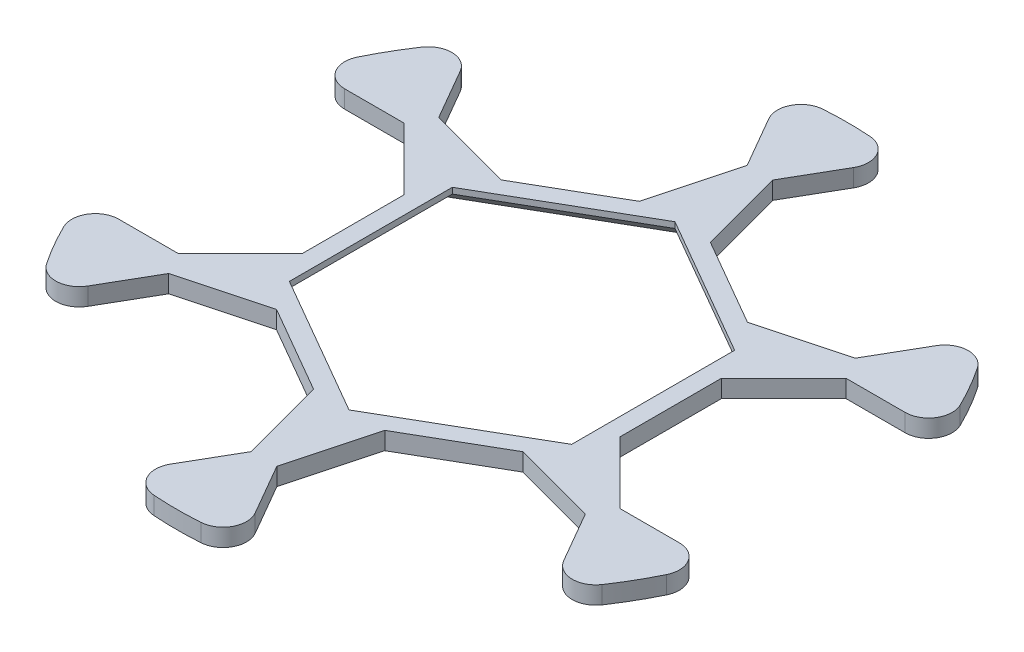
SolidWorks part; units mm, degrees
ref_plane "Front Plane" through (0, 0, 0) normal (0, 0, 1) x (1, 0, 0)
ref_plane "Top Plane" through (0, 0, 0) normal (0, 1, 0) x (1, 0, 0)
ref_plane "Right Plane" through (0, 0, 0) normal (1, 0, 0) x (0, 0, -1)
sketch "Sketch1" plane through (0, 0, 0) normal (0, 1, 0) x (1, 0, 0)
  circle A0 centre (0, 0) radius 28.5
  circle A1 centre (0, 0) radius 12.7
  dimension "D1" = 57
  dimension "D2" = 25.4
extrude "Boss-Extrude1" add sketch "Sketch1" along normal blind 2
sketch "Sketch2" plane through (0, 2, 0) normal (0, 1, 0) x (1, 0, 0)
  circle A1 centre (0, 0) radius 28.5 construction
  circle A2 centre (0, 0) radius 28.5
extrude "Boss-Extrude2" add sketch "Sketch2" along normal blind 1
sketch "Sketch3" plane through (0, 3, 0) normal (0, 1, 0) x (1, 0, 0)
  circle A0 centre (0, 0) radius 11
  dimension "D1" = 22
extrude "Boss-Extrude3" add sketch "Sketch3" along normal blind 7
sketch "Sketch4" plane through (0, 10, 0) normal (0, 1, 0) x (1, 0, 0)
  circle A0 centre (0, 0) radius 9.65
  dimension "D1" = 19.3
extrude "Cut-Extrude1" cut sketch "Sketch4" against normal through all both and the other way through all
sketch "Sketch5" plane through (0, 10, 0) normal (0, 1, 0) x (1, 0, 0)
  circle A0 centre (0, 0) radius 11
  circle A1 centre (0, 0) radius 8
  dimension "D1" = 16
extrude "Boss-Extrude4" add sketch "Sketch5" along normal blind 5
sketch "Sketch6" plane through (0, 2, 0) normal (0, -1, 0) x (1, 0, 0)
  circle A0 centre (0, 0) radius 9.65 construction
  circle A1 centre (0, 0) radius 12.7
  circle A2 centre (0, 0) radius 12.7
  circle A3 centre (0, 0) radius 9.65
  dimension "D1" = 0
extrude "Boss-Extrude5" add sketch "Sketch6" along normal up to surface (2 mm away) up to face at (0, 0, 28.5)
sketch "Sketch11" plane through (0, 3, 0) normal (0, 1, 0) x (1, 0, 0)
  line L1 (-14.6647, 0) -> (-7.3323, -12.7)
  line L2 (-7.3323, -12.7) -> (7.3323, -12.7)
  line L3 (7.3323, -12.7) -> (14.6647, 0)
  line L4 (14.6647, 0) -> (7.3323, 12.7)
  line L5 (7.3323, 12.7) -> (-7.3323, 12.7)
  line L6 (-7.3323, 12.7) -> (-14.6647, 0)
  circle A0 centre (0, 0) radius 12.7 construction
  circle A1 centre (0, 0) radius 11 construction
  circle A2 centre (0, 0) radius 11
  dimension "D1" = 25.4
sketch "Sketch13" plane through (0, 0, 0) normal (0, -1, 0) x (1, 0, 0)
  circle A1 centre (0, 0) radius 28.5
  circle A2 centre (0, 0) radius 28.5
  dimension "D1" = 0
extrude "Cut-Extrude2" cut sketch "Sketch13" against normal blind 1
sketch "Sketch12" plane through (0, 1, 0) normal (0, -1, 0) x (1, 0, 0)
  line L0 (25.5, 0) -> (-25.5, 0) construction
  line L2 (26.5, -2) -> (24.5, -2)
  line L3 (26.5, -2) -> (26.5, 2)
  line L4 (26.5, 2) -> (24.5, 2)
  line L5 (24.5, -2) -> (24.5, 2)
  line L6 (26.5, -2) -> (24.5, 2) construction
  line L7 (26.5, 2) -> (24.5, -2) construction
  line L8 (-26.5, -2) -> (-24.5, -2)
  line L9 (-26.5, -2) -> (-26.5, 2)
  line L10 (-26.5, 2) -> (-24.5, 2)
  line L11 (-24.5, -2) -> (-24.5, 2)
  line L12 (-26.5, -2) -> (-24.5, 2) construction
  line L13 (-26.5, 2) -> (-24.5, -2) construction
  point P4 (0, 0)
  dimension "D1" = 51
  dimension "D2" = 2
  dimension "D3" = 4
  dimension "D4" = 2
  dimension "D5" = 4
extrude "Boss-Extrude7" add sketch "Sketch12" along normal blind 2
fillet "Fillet1" radius 0.5 8 edges at (-26.5, 0, 2) (-26.5, 0, -2) (-24.5, 0, -2) (-24.5, 0, 2) (26.5, 0, 2) (26.5, 0, -2) (24.5, 0, -2) (24.5, 0, 2)
sketch "Sketch14" plane through (0, 3, 0) normal (0, 1, 0) x (1, 0, 0)
  circle A0 centre (0, 0) radius 11 construction
  circle A1 centre (0, 0) radius 28.5
  circle A2 centre (0, 0) radius 28.5
  circle A3 centre (0, 0) radius 11
  dimension "D1" = 0
extrude "Boss-Extrude8" add sketch "Sketch14" along normal blind 0.35
sketch "Sketch15" plane through (0, 3.35, 0) normal (0, 1, 0) x (1, 0, 0)
  line L1 (0, -12.9904) -> (11.25, -6.4952)
  line L2 (11.25, -6.4952) -> (11.25, 6.4952)
  line L3 (11.25, 6.4952) -> (0, 12.9904)
  line L4 (0, 12.9904) -> (-11.25, 6.4952)
  line L5 (-11.25, 6.4952) -> (-11.25, -6.4952)
  line L6 (-11.25, -6.4952) -> (0, -12.9904)
  circle A0 centre (0, 0) radius 11.25 construction
  circle A2 centre (0, 0) radius 9.65 construction
  circle A3 centre (0, 0) radius 9.65
  dimension "D1" = 22.5
extrude "Boss-Extrude9" add sketch "Sketch15" along normal up to surface (11.65 mm away) up to face at (0, 15, 11)
sketch "Sketch16" plane through (0, 3.35, 0) normal (0, 1, 0) x (1, 0, 0)
  line L0 (0, 0) -> (0, -28.5) construction
  line L1 (0, 0) -> (-11.25, -6.4952) construction
  line L2 (-11.25, -6.4952) -> (-24.6817, -14.25) construction
  line L3 (0, -28.5) -> (-24.6817, -14.25) construction
  line L4 (-14.25, -24.6817) -> (-6.75, -11.6913) construction
  line L5 (-12.3409, -21.375) -> (-14.25, -24.6817) construction
  line L6 (-6.3692, -29.2317) -> (-22.1308, -20.1317) construction
  line L8 (-6.3692, -29.2317) -> (-2.3692, -22.3035) construction
  line L10 (-2.3692, -22.3035) -> (-4.1993, -15.4734) construction
  line L11 (-11.3007, -11.3734) -> (-18.1308, -13.2035) construction
  line L12 (-6.1862, -29.9147) -> (-22.8138, -20.3147)
  line L13 (-4.1993, -15.4734) -> (-11.3007, -11.3734) construction
  line L14 (-18.1308, -13.2035) -> (-22.1308, -20.1317) construction
  line L17 (-3.7699, -15.1439) -> (-11.2301, -10.8368) construction
  line L50 (-3.7699, -15.1439) -> (-11.2301, -10.8368) construction
  line L51 (-11.2301, -10.8368) -> (-18.4603, -12.7742) construction
  line L52 (-1.8326, -22.3742) -> (-3.7699, -15.1439) construction
  line L53 (-3.0261, -13.8413) -> (-10.4739, -9.5413)
  line L54 (-10.4739, -9.5413) -> (-17.7138, -11.4813)
  line L55 (-3.0261, -13.8413) -> (-1.0862, -21.0813)
  line L56 (-22.8138, -20.3147) -> (-17.7138, -11.4813)
  line L57 (-6.1862, -29.9147) -> (-1.8326, -22.3742) construction
  line L58 (-18.4603, -12.7742) -> (-22.8138, -20.3147) construction
  line L59 (-6.1862, -29.9147) -> (-1.0862, -21.0813)
  line L60 (-13.5, -4.3) -> (-18.8, -9.6)
  line L61 (-29, -9.6) -> (-18.8, -9.6)
  line L62 (-29, -9.6) -> (-29, 9.6)
  line L63 (-29, 9.6) -> (-18.8, 9.6)
  line L64 (-13.5, 4.3) -> (-18.8, 9.6)
  line L65 (-13.5, -4.3) -> (-13.5, 4.3)
  line L66 (-10.4739, 9.5413) -> (-17.7138, 11.4813)
  line L67 (-22.8138, 20.3147) -> (-17.7138, 11.4813)
  line L68 (-22.8138, 20.3147) -> (-6.1862, 29.9147)
  line L69 (-6.1862, 29.9147) -> (-1.0862, 21.0813)
  line L70 (-3.0261, 13.8413) -> (-1.0862, 21.0813)
  line L71 (-10.4739, 9.5413) -> (-3.0261, 13.8413)
  line L72 (3.0261, 13.8413) -> (1.0862, 21.0813)
  line L73 (6.1862, 29.9147) -> (1.0862, 21.0813)
  line L74 (6.1862, 29.9147) -> (22.8138, 20.3147)
  line L75 (22.8138, 20.3147) -> (17.7138, 11.4813)
  line L76 (10.4739, 9.5413) -> (17.7138, 11.4813)
  line L77 (3.0261, 13.8413) -> (10.4739, 9.5413)
  line L78 (13.5, 4.3) -> (18.8, 9.6)
  line L79 (29, 9.6) -> (18.8, 9.6)
  line L80 (29, 9.6) -> (29, -9.6)
  line L81 (29, -9.6) -> (18.8, -9.6)
  line L82 (13.5, -4.3) -> (18.8, -9.6)
  line L83 (13.5, 4.3) -> (13.5, -4.3)
  line L84 (10.4739, -9.5413) -> (17.7138, -11.4813)
  line L85 (22.8138, -20.3147) -> (17.7138, -11.4813)
  line L86 (22.8138, -20.3147) -> (6.1862, -29.9147)
  line L87 (6.1862, -29.9147) -> (1.0862, -21.0813)
  line L88 (3.0261, -13.8413) -> (1.0862, -21.0813)
  line L89 (10.4739, -9.5413) -> (3.0261, -13.8413)
  circle A0 centre (0, 0) radius 28.5 construction
  point P15 (-14.25, -24.6817)
  point P17 (-6.75, -11.6913)
  point P62 (-6.75, -11.6913)
  point P64 (0, 0)
  dimension "D1" = 15
  dimension "D2" = 90
  dimension "D3" = 18.2
  dimension "D4" = 0.5
  dimension "D5" = 6
  dimension "D6" = 90
  dimension "D7" = 8.6
  dimension "D8" = 135
  dimension "D9" = 135
extrude "Cut-Extrude3" cut sketch "Sketch16" against normal blind 1.5
chamfer "Chamfer1" distance 1 angle 45 1 edges at (0, 10, 8)
fillet "Fillet2" radius 2 12 edges at (5.1034, 2.6, -28.0394) (21.7311, 2.6, -18.4394) (26.8345, 2.6, -9.6) (26.8345, 2.6, 9.6) (5.1034, 2.6, 28.0394) (21.7311, 2.6, 18.4394) (-5.1034, 2.6, 28.0394) (-21.7311, 2.6, 18.4394) (-26.8345, 2.6, 9.6) (-26.8345, 2.6, -9.6) (-21.7311, 2.6, -18.4394) (-5.1034, 2.6, -28.0394)
sketch "Sketch17" plane through (0, 1, 0) normal (0, -1, 0) x (1, 0, 0)
  circle A0 centre (0, 0) radius 9.67
  circle A1 centre (0, 0) radius 9.65 construction
  dimension "D1" = 0.02
extrude "Cut-Extrude4" cut sketch "Sketch17" against normal up to surface (9 mm away) up to face at (0, 10, 9)
pattern_circular "CirPattern1" count 2 every 30 about axis through (0, 0, 0) along (0, 1, 0) of "Boss-Extrude7"
sketch "Sketch18" plane through (0, 1, 0) normal (0, -1, 0) x (1, 0, 0)
  line L0 (26.3536, -1.8536) -> (24.6464, 1.8536) construction
  line L1 (-24.6464, -1.8536) -> (-26.3536, 1.8536) construction
  line L3 (-24.0999, -2.4552) -> (-26.9001, -2.4552)
  line L4 (-24.0999, -2.4552) -> (-24.0999, 2.4552)
  line L5 (-24.0999, 2.4552) -> (-26.9001, 2.4552)
  line L6 (-26.9001, -2.4552) -> (-26.9001, 2.4552)
  line L7 (-24.0999, -2.4552) -> (-26.9001, 2.4552) construction
  line L8 (-24.0999, 2.4552) -> (-26.9001, -2.4552) construction
  line L9 (26.9286, -2.8374) -> (24.0714, -2.8374)
  line L10 (26.9286, -2.8374) -> (26.9286, 2.8374)
  line L11 (26.9286, 2.8374) -> (24.0714, 2.8374)
  line L12 (24.0714, -2.8374) -> (24.0714, 2.8374)
  line L13 (26.9286, -2.8374) -> (24.0714, 2.8374) construction
  line L14 (26.9286, 2.8374) -> (24.0714, -2.8374) construction
  arc A0 (26, -2) -> (26.5, -1.5) centre (26, -1.5) ccw construction
  arc A1 (25, 2) -> (24.5, 1.5) centre (25, 1.5) ccw construction
  arc A2 (-25, -2) -> (-24.5, -1.5) centre (-25, -1.5) ccw construction
  arc A3 (-26, 2) -> (-26.5, 1.5) centre (-26, 1.5) ccw construction
  point P16 (-25.5, 0)
  point P21 (25.5, 0)
extrude "Cut-Extrude5" cut sketch "Sketch18" along normal blind 10
sketch "Sketch19" plane through (0, 1, 0) normal (0, -1, 0) x (1, 0, 0)
  line L0 (21.9497, 14.9821) -> (20.2176, 13.9821) construction
  line L1 (23.9497, 11.5179) -> (21.9497, 14.9821) construction
  line L2 (20.2176, 13.9821) -> (22.2176, 10.5179) construction
  line L3 (22.2176, 10.5179) -> (23.9497, 11.5179) construction
  line L4 (-23.9497, -11.5179) -> (-21.9497, -14.9821) construction
  line L5 (-21.9497, -14.9821) -> (-20.2176, -13.9821) construction
  line L6 (-20.2176, -13.9821) -> (-22.2176, -10.5179) construction
  line L7 (-22.2176, -10.5179) -> (-23.9497, -11.5179) construction
  line L8 (21.9497, 14.9821) -> (20.2176, 13.9821)
  line L9 (23.9497, 11.5179) -> (21.9497, 14.9821)
  line L10 (20.2176, 13.9821) -> (22.2176, 10.5179)
  line L11 (22.2176, 10.5179) -> (23.9497, 11.5179)
  line L12 (-23.9497, -11.5179) -> (-21.9497, -14.9821)
  line L13 (-21.9497, -14.9821) -> (-20.2176, -13.9821)
  line L14 (-20.2176, -13.9821) -> (-22.2176, -10.5179)
  line L15 (-22.2176, -10.5179) -> (-23.9497, -11.5179)
  circle A1 centre (0, 0) radius 28.5
  circle A2 centre (0, 0) radius 28.5
  dimension "D1" = 0
extrude "Cut-Extrude6" cut sketch "Sketch19" against normal up to vertex (0.85 mm away)
fillet "Fillet3" radius 0.5 8 edges at (20.2176, 0.425, 13.9821) (22.2176, 0.425, 10.5179) (23.9497, 0.425, 11.5179) (21.9497, 0.425, 14.9821) (-20.2176, 0.425, -13.9821) (-22.2176, 0.425, -10.5179) (-23.9497, 0.425, -11.5179) (-21.9497, 0.425, -14.9821)
sketch "Sketch20" plane through (0, -1, 0) normal (0, -1, 0) x (1, 0, 0)
  circle A0 centre (0, 0) radius 68.6472
extrude "Cut-Extrude7" cut sketch "Sketch20" against normal blind 0.7
sketch "Sketch21" plane through (0, 3.35, 0) normal (0, 1, 0) x (1, 0, 0)
  line L1 (0, 13.8564) -> (-12, 6.9282)
  line L2 (-12, 6.9282) -> (-12, -6.9282)
  line L3 (-12, -6.9282) -> (0, -13.8564)
  line L4 (0, -13.8564) -> (12, -6.9282)
  line L5 (12, -6.9282) -> (12, 6.9282)
  line L6 (12, 6.9282) -> (0, 13.8564)
  circle A0 centre (0, 0) radius 12 construction
  dimension "D1" = 24
extrude "Cut-Extrude8" cut sketch "Sketch21" against normal through all both and the other way through all
sketch "Sketch22" plane through (0, 1.85, 0) normal (0, -1, 0) x (1, 0, 0)
  line L30 (3.5993, -25.4341) -> (1.0862, -21.0813)
  line L31 (1.0862, -21.0813) -> (3.0261, -13.8413)
  line L32 (3.0261, -13.8413) -> (10.4739, -9.5413)
  line L33 (10.4739, -9.5413) -> (17.7138, -11.4813)
  line L34 (17.7138, -11.4813) -> (20.227, -15.8341)
  line L35 (23.8262, -9.6) -> (18.8, -9.6)
  line L36 (18.8, -9.6) -> (13.5, -4.3)
  line L37 (13.5, -4.3) -> (13.5, 4.3)
  line L38 (13.5, 4.3) -> (18.8, 9.6)
  line L39 (18.8, 9.6) -> (23.8262, 9.6)
  line L40 (20.227, 15.8341) -> (17.7138, 11.4813)
  line L41 (17.7138, 11.4813) -> (10.4739, 9.5413)
  line L42 (10.4739, 9.5413) -> (3.0261, 13.8413)
  line L43 (3.0261, 13.8413) -> (1.0862, 21.0813)
  line L44 (1.0862, 21.0813) -> (3.5993, 25.4341)
  line L45 (-3.5993, 25.4341) -> (-1.0862, 21.0813)
  line L46 (-1.0862, 21.0813) -> (-3.0261, 13.8413)
  line L47 (-3.0261, 13.8413) -> (-10.4739, 9.5413)
  line L48 (-10.4739, 9.5413) -> (-17.7138, 11.4813)
  line L49 (-17.7138, 11.4813) -> (-20.227, 15.8341)
  line L50 (-23.8262, 9.6) -> (-18.8, 9.6)
  line L51 (-18.8, 9.6) -> (-13.5, 4.3)
  line L52 (-13.5, 4.3) -> (-13.5, -4.3)
  line L53 (-13.5, -4.3) -> (-18.8, -9.6)
  line L54 (-18.8, -9.6) -> (-23.8262, -9.6)
  line L55 (-20.227, -15.8341) -> (-17.7138, -11.4813)
  line L56 (-17.7138, -11.4813) -> (-10.4739, -9.5413)
  line L57 (-10.4739, -9.5413) -> (-3.0261, -13.8413)
  line L58 (-3.0261, -13.8413) -> (-1.0862, -21.0813)
  line L59 (-1.0862, -21.0813) -> (-3.5993, -25.4341)
  line L60 (3.5993, -25.4341) -> (1.0862, -21.0813)
  line L61 (1.0862, -21.0813) -> (3.0261, -13.8413)
  line L62 (3.0261, -13.8413) -> (10.4739, -9.5413)
  line L63 (10.4739, -9.5413) -> (17.7138, -11.4813)
  line L64 (17.7138, -11.4813) -> (20.227, -15.8341)
  line L65 (23.8262, -9.6) -> (18.8, -9.6)
  line L66 (18.8, -9.6) -> (13.5, -4.3)
  line L67 (13.5, -4.3) -> (13.5, 4.3)
  line L68 (13.5, 4.3) -> (18.8, 9.6)
  line L69 (18.8, 9.6) -> (23.8262, 9.6)
  line L70 (20.227, 15.8341) -> (17.7138, 11.4813)
  line L71 (17.7138, 11.4813) -> (10.4739, 9.5413)
  line L72 (10.4739, 9.5413) -> (3.0261, 13.8413)
  line L73 (3.0261, 13.8413) -> (1.0862, 21.0813)
  line L74 (1.0862, 21.0813) -> (3.5993, 25.4341)
  line L75 (-3.5993, 25.4341) -> (-1.0862, 21.0813)
  line L76 (-1.0862, 21.0813) -> (-3.0261, 13.8413)
  line L77 (-3.0261, 13.8413) -> (-10.4739, 9.5413)
  line L78 (-10.4739, 9.5413) -> (-17.7138, 11.4813)
  line L79 (-17.7138, 11.4813) -> (-20.227, 15.8341)
  line L80 (-23.8262, 9.6) -> (-18.8, 9.6)
  line L81 (-18.8, 9.6) -> (-13.5, 4.3)
  line L82 (-13.5, 4.3) -> (-13.5, -4.3)
  line L83 (-13.5, -4.3) -> (-18.8, -9.6)
  line L84 (-18.8, -9.6) -> (-23.8262, -9.6)
  line L85 (-20.227, -15.8341) -> (-17.7138, -11.4813)
  line L86 (-17.7138, -11.4813) -> (-10.4739, -9.5413)
  line L87 (-10.4739, -9.5413) -> (-3.0261, -13.8413)
  line L88 (-3.0261, -13.8413) -> (-1.0862, -21.0813)
  line L89 (-1.0862, -21.0813) -> (-3.5993, -25.4341)
  arc A18 (20.227, -15.8341) -> (23.6163, -15.9537) centre (21.959, -14.8341) ccw
  arc A19 (23.6163, -15.9537) -> (25.6245, -12.4755) centre (0, 0) ccw
  arc A20 (25.6245, -12.4755) -> (23.8262, -9.6) centre (23.8262, -11.6) ccw
  arc A21 (23.8262, 9.6) -> (25.6245, 12.4755) centre (23.8262, 11.6) ccw
  arc A22 (25.6245, 12.4755) -> (23.6163, 15.9537) centre (0, 0) ccw
  arc A23 (23.6163, 15.9537) -> (20.227, 15.8341) centre (21.959, 14.8341) ccw
  arc A24 (3.5993, 25.4341) -> (2.0082, 28.4292) centre (1.8672, 26.4341) ccw
  arc A25 (2.0082, 28.4292) -> (-2.0082, 28.4292) centre (0, 0) ccw
  arc A26 (-2.0082, 28.4292) -> (-3.5993, 25.4341) centre (-1.8672, 26.4341) ccw
  arc A27 (-20.227, 15.8341) -> (-23.6163, 15.9537) centre (-21.959, 14.8341) ccw
  arc A28 (-23.6163, 15.9537) -> (-25.6245, 12.4755) centre (0, 0) ccw
  arc A29 (-25.6245, 12.4755) -> (-23.8262, 9.6) centre (-23.8262, 11.6) ccw
  arc A30 (-23.8262, -9.6) -> (-25.6245, -12.4755) centre (-23.8262, -11.6) ccw
  arc A31 (-25.6245, -12.4755) -> (-23.6163, -15.9537) centre (0, 0) ccw
  arc A32 (-23.6163, -15.9537) -> (-20.227, -15.8341) centre (-21.959, -14.8341) ccw
  arc A33 (-3.5993, -25.4341) -> (-2.0082, -28.4292) centre (-1.8672, -26.4341) ccw
  arc A34 (-2.0082, -28.4292) -> (2.0082, -28.4292) centre (0, 0) ccw
  arc A35 (2.0082, -28.4292) -> (3.5993, -25.4341) centre (1.8672, -26.4341) ccw
  arc A36 (20.227, -15.8341) -> (23.6163, -15.9537) centre (21.959, -14.8341) ccw
  arc A37 (23.6163, -15.9537) -> (25.6245, -12.4755) centre (0, 0) ccw
  arc A38 (25.6245, -12.4755) -> (23.8262, -9.6) centre (23.8262, -11.6) ccw
  arc A39 (23.8262, 9.6) -> (25.6245, 12.4755) centre (23.8262, 11.6) ccw
  arc A40 (25.6245, 12.4755) -> (23.6163, 15.9537) centre (0, 0) ccw
  arc A41 (23.6163, 15.9537) -> (20.227, 15.8341) centre (21.959, 14.8341) ccw
  arc A42 (3.5993, 25.4341) -> (2.0082, 28.4292) centre (1.8672, 26.4341) ccw
  arc A43 (2.0082, 28.4292) -> (-2.0082, 28.4292) centre (0, 0) ccw
  arc A44 (-2.0082, 28.4292) -> (-3.5993, 25.4341) centre (-1.8672, 26.4341) ccw
  arc A45 (-20.227, 15.8341) -> (-23.6163, 15.9537) centre (-21.959, 14.8341) ccw
  arc A46 (-23.6163, 15.9537) -> (-25.6245, 12.4755) centre (0, 0) ccw
  arc A47 (-25.6245, 12.4755) -> (-23.8262, 9.6) centre (-23.8262, 11.6) ccw
  arc A48 (-23.8262, -9.6) -> (-25.6245, -12.4755) centre (-23.8262, -11.6) ccw
  arc A49 (-25.6245, -12.4755) -> (-23.6163, -15.9537) centre (0, 0) ccw
  arc A50 (-23.6163, -15.9537) -> (-20.227, -15.8341) centre (-21.959, -14.8341) ccw
  arc A51 (-3.5993, -25.4341) -> (-2.0082, -28.4292) centre (-1.8672, -26.4341) ccw
  arc A52 (-2.0082, -28.4292) -> (2.0082, -28.4292) centre (0, 0) ccw
  arc A53 (2.0082, -28.4292) -> (3.5993, -25.4341) centre (1.8672, -26.4341) ccw
  dimension "D1" = 0
extrude "Cut-Extrude9" cut sketch "Sketch22" along normal blind 10
chamfer "Chamfer2" distance 1 angle 45 6 edges at (-6, 1.85, 10.3923) (-12, 1.85, 0) (-6, 1.85, -10.3923) (6, 1.85, -10.3923) (12, 1.85, 0) (6, 1.85, 10.3923)
equation "\"Fin1_Outer_Diameter\"= 45"
equation "\"Fin1_Inner_Diameter\"= 14"
equation "\"Fin_Gap\"= 1"
equation "\"D1@Sketch1\"=\"Fin1_Outer_Diameter\"+12"
equation "\"D1@Sketch12\"=\"Fin1_Outer_Diameter\"+6"
